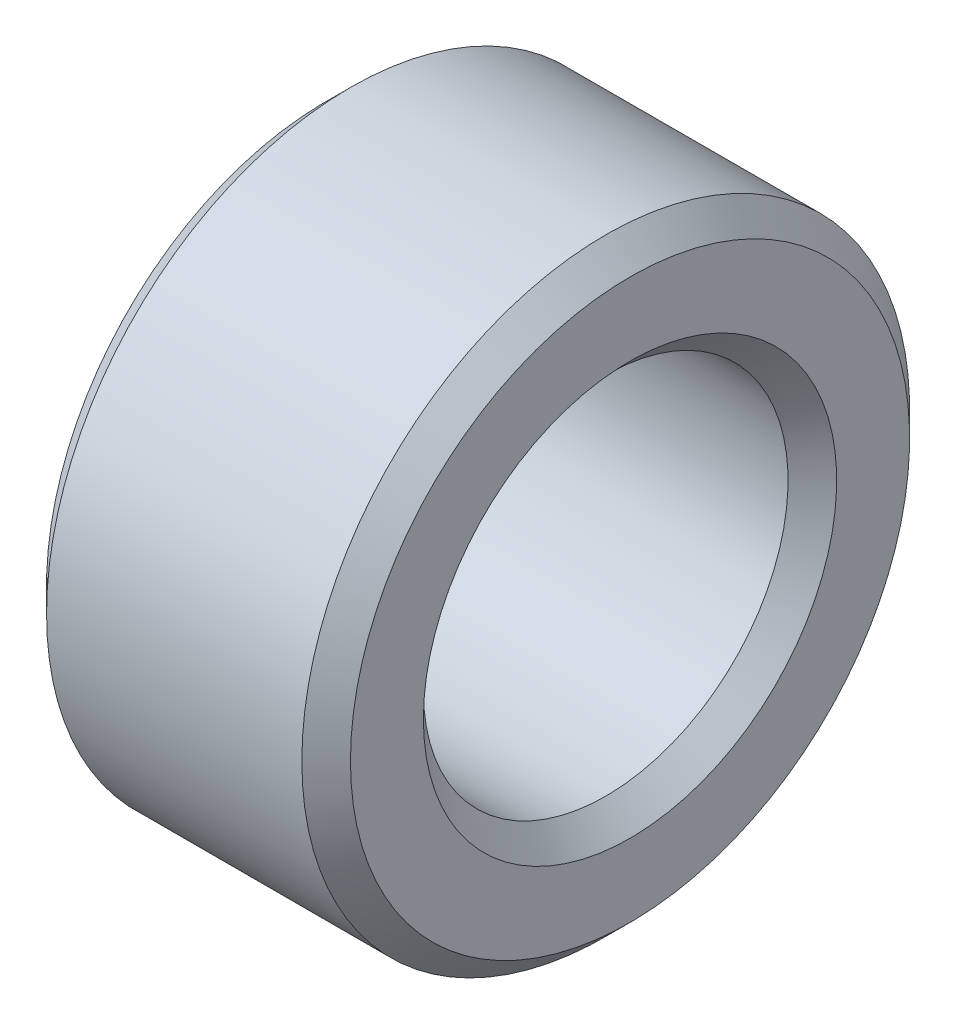
SolidWorks part; units mm, degrees
material "S45C相当"
ref_plane "Front Plane" through (0, 0, 0) normal (0, 0, 1) x (1, 0, 0)
ref_plane "Top Plane" through (0, 0, 0) normal (0, 1, 0) x (1, 0, 0)
ref_plane "Right Plane" through (0, 0, 0) normal (1, 0, 0) x (0, 0, -1)
sketch "Sketch1" plane through (0, 0, 0) normal (0, 0, 1) x (1, 0, 0)
  line L0 (0, 0) -> (2.5, 0) construction
  line L2 (0, 1.5) -> (2.5, 1.5)
  line L3 (0, 1.5) -> (0, 2.5)
  line L4 (0, 2.5) -> (2.5, 2.5)
  line L5 (2.5, 1.5) -> (2.5, 2.5)
  dimension "D" = 5
  dimension "V" = 3
  dimension "T" = 2.5
revolve "Revolve1" add sketch "Sketch1" angle 360 about L0
chamfer "Chamfer1" distance 0.2 angle 45 4 edges at (0, 0, 2.5) (2.5, 0, 2.5) (2.5, 0, 1.5) (0, 0, 1.5)
